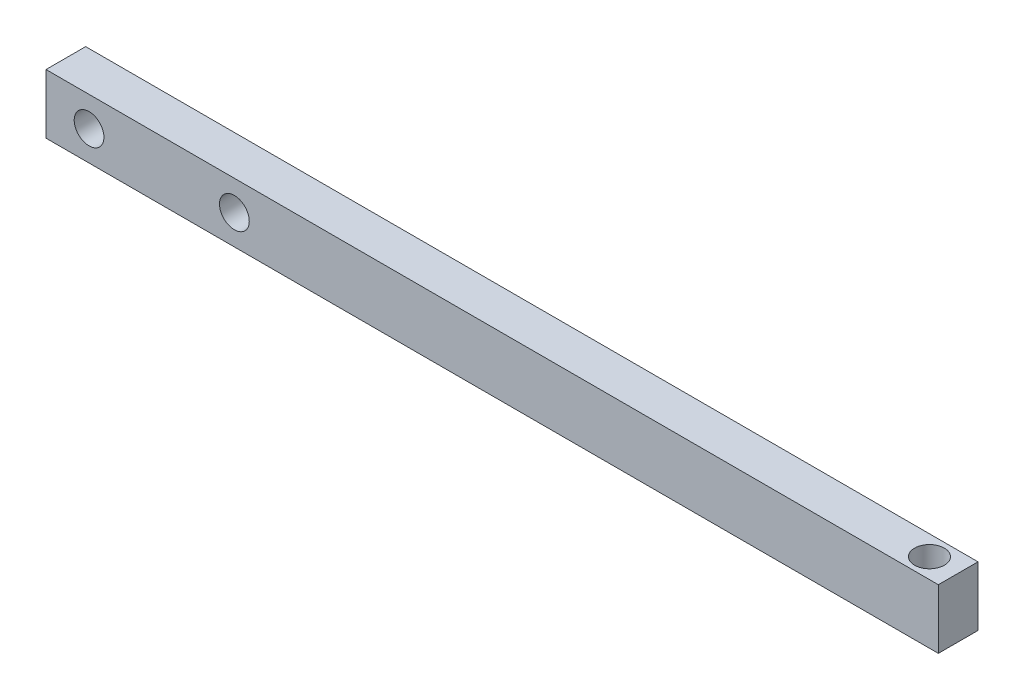
SolidWorks part; units mm, degrees
ref_plane "Alzado" through (0, 0, 0) normal (0, 0, 1) x (1, 0, 0)
ref_plane "Planta" through (0, 0, 0) normal (0, 1, 0) x (1, 0, 0)
ref_plane "Vista lateral" through (0, 0, 0) normal (1, 0, 0) x (0, 0, -1)
sketch "Croquis1" plane through (0, 0, 0) normal (0, 0, 1) x (1, 0, 0)
  line L1 (508, -38.1) -> (-508, -38.1)
  line L2 (508, -38.1) -> (508, 38.1)
  line L3 (508, 38.1) -> (-508, 38.1)
  line L4 (-508, -38.1) -> (-508, 38.1)
  line L5 (508, -38.1) -> (-508, 38.1) construction
  line L6 (508, 38.1) -> (-508, -38.1) construction
  point P0 (0, 0)
  dimension "D1" = 1016
  dimension "D2" = 76.2
extrude "Saliente-Extruir1" add sketch "Croquis1" along normal blind 50.8
sketch "Croquis2" plane through (0, 0, 50.8) normal (0, 0, 1) x (1, 0, 0)
  line L0 (-508, -38.1) -> (508, -38.1) construction
  line L1 (-508, 38.1) -> (-431.8, 38.1)
  line L2 (-508, 38.1) -> (-508, -38.1)
  line L3 (-508, -38.1) -> (-431.8, -38.1)
  line L4 (-431.8, 38.1) -> (-431.8, -38.1)
  line L5 (508, 38.1) -> (-508, 38.1) construction
  line L6 (-431.8, -38.1) -> (-355.6, -38.1)
  line L7 (-431.8, -38.1) -> (-431.8, 38.1)
  line L8 (-431.8, 38.1) -> (-355.6, 38.1)
  line L9 (-355.6, -38.1) -> (-355.6, 38.1)
  line L10 (-355.6, 38.1) -> (-431.8, -38.1) construction
  line L11 (-431.8, 38.1) -> (-355.6, -38.1) construction
  circle A0 centre (-393.7, 0) radius 19.05
  dimension "D3" = 38.1
  dimension "D1" = 76.2
  dimension "D2" = 76.2
extrude "Cortar-Extruir1" cut sketch "Croquis2" against normal through all contours A0
sketch "Croquis5" plane through (0, 38.1, 0) normal (0, 1, 0) x (1, 0, 0)
  circle A0 centre (471.227, -25.4) radius 19.05
  dimension "D1" = 38.1
extrude "Cortar-Extruir3" cut sketch "Croquis5" against normal through all
sketch "Croquis6" plane through (-508, 0, 0) normal (-1, 0, 0) x (0, 0, 1)
  line L1 (0, 38.1) -> (50.8, 38.1)
  line L2 (0, 38.1) -> (0, -38.1)
  line L3 (0, -38.1) -> (50.8, -38.1)
  line L4 (50.8, 38.1) -> (50.8, -38.1)
extrude "Saliente-Extruir2" add sketch "Croquis6" along normal blind 127
sketch "Croquis7" plane through (0, 0, 50.8) normal (0, 0, 1) x (1, 0, 0)
  circle A0 centre (-579.8459, 0) radius 19.05
  dimension "D1" = 38.1
extrude "Cortar-Extruir4" cut sketch "Croquis7" against normal through all
